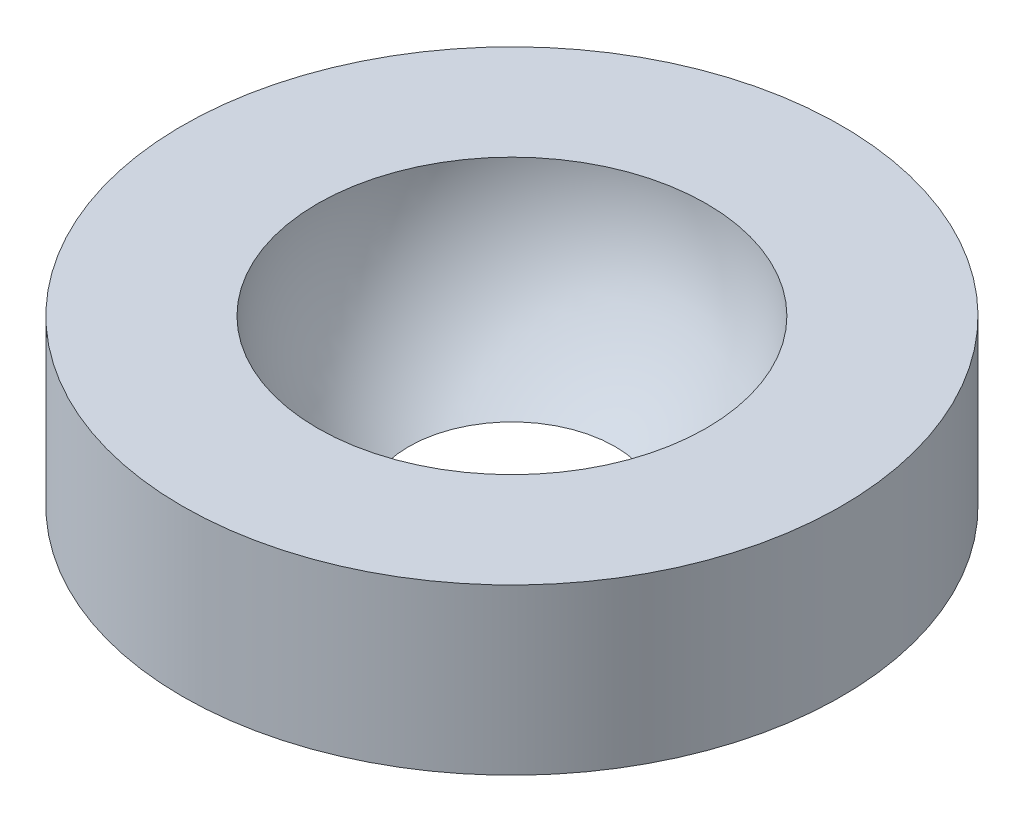
SolidWorks part; units mm, degrees
ref_plane "Front Plane" through (0, 0, 0) normal (0, 0, 1) x (1, 0, 0)
ref_plane "Top Plane" through (0, 0, 0) normal (0, 1, 0) x (1, 0, 0)
ref_plane "Right Plane" through (0, 0, 0) normal (1, 0, 0) x (0, 0, -1)
sketch "Sketch1" plane through (0, 0, 0) normal (0, 0, 1) x (1, 0, 0)
  line L0 (0, 12.1169) -> (0, -15.8948) construction
  line L1 (12.7, -6.35) -> (3.9778, -6.35)
  line L2 (12.7, 0) -> (7.493, 0)
  line L3 (12.7, 0) -> (12.7, -6.35)
  circle A0 centre (0, 0) radius 7.493 construction
  arc A1 (3.9778, -6.35) -> (7.493, 0) centre (0, 0) ccw
  dimension "D1" = 14.986
  dimension "D2" = 12.7
  dimension "D3" = 6.35
revolve "Revolve1" add sketch "Sketch1" angle 360 about L0
